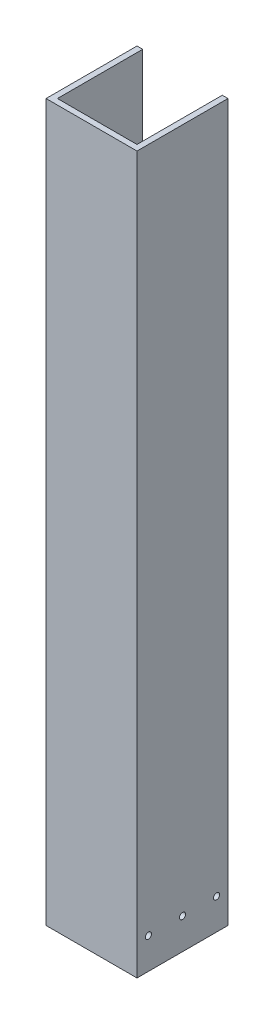
SolidWorks part; units mm, degrees
ref_plane "Front Plane" through (0, 0, 0) normal (0, 0, 1) x (1, 0, 0)
ref_plane "Top Plane" through (0, 0, 0) normal (0, 1, 0) x (1, 0, 0)
ref_plane "Right Plane" through (0, 0, 0) normal (1, 0, 0) x (0, 0, -1)
sketch "Sketch1" plane through (0, 0, 0) normal (0, 1, 0) x (1, 0, 0)
  line L0 (0, 0) -> (0, -50.8)
  line L1 (0, -50.8) -> (50.8, -50.8)
  line L2 (50.8, -50.8) -> (50.8, 0)
  line L3 (50.8, 0) -> (47.625, 0)
  line L4 (47.625, 0) -> (47.625, -47.625)
  line L5 (47.625, -47.625) -> (3.175, -47.625)
  line L6 (3.175, -47.625) -> (3.175, 0)
  line L7 (3.175, 0) -> (0, 0)
  dimension "D1" = 50.8
  dimension "D2" = 3.175
  dimension "D3" = 3.175
  dimension "D4" = 3.175
  dimension "D5" = 50.8
extrude "Boss-Extrude1" add sketch "Sketch1" along normal blind 400
sketch "Sketch2" plane through (0, 0, 0) normal (0, 0, -1) x (-1, 0, 0)
  line L0 (-50.8, 400) -> (-50.8, 0) construction
  line L1 (-47.625, 400) -> (-47.625, 0) construction
  line L2 (-50.8, 349.2) -> (-47.625, 349.2)
  line L3 (-50.8, 349.2) -> (-50.8, 323.8)
  line L4 (-50.8, 323.8) -> (-47.625, 323.8)
  line L5 (-47.625, 349.2) -> (-47.625, 323.8)
  line L6 (-50.8, 400) -> (-47.625, 400) construction
  dimension "D1" = 25.4
  dimension "D2" = 50.8
hole_wizard "Tap Drill for #8-32 Tap1" positions "Sketch4" profile "Sketch3" hole size "#8-32" standard "ANSI Inch" end condition through all
sketch "Sketch4" plane through (50.8, 0, 0) normal (1, 0, 0) x (0, 0, -1)
  point P0 (-44.45, 17.3)
  point P3 (-25.4, 17.3)
  point P6 (-6.35, 17.3)
sketch "Sketch3" plane through (50.8, 17.3, 44.45) normal (0, 1, 0) x (0, 0, -1)
  line L0 (0, 0) -> (0, 50.8)
  line L1 (0, 50.8) -> (1.7272, 50.8)
  line L2 (1.7272, 50.8) -> (1.7272, 0)
  line L5 (1.7272, 0) -> (0, 0)
  line L11 (0, -6.35) -> (0, 107.95) construction
  dimension "Thru Hole Dia." = 3.4544
  dimension "Thru Hole Depth" = 50.8
